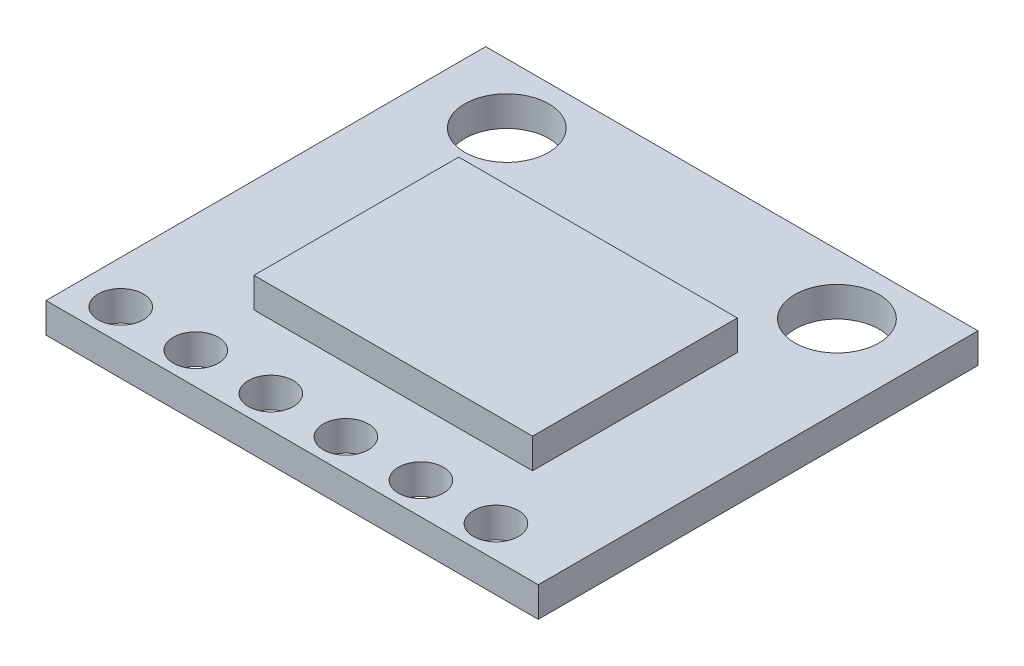
SolidWorks part; units mm, degrees
ref_plane "Front Plane" through (0, 0, 0) normal (0, 0, 1) x (1, 0, 0)
ref_plane "Top Plane" through (0, 0, 0) normal (0, 1, 0) x (1, 0, 0)
ref_plane "Right Plane" through (0, 0, 0) normal (1, 0, 0) x (0, 0, -1)
sketch "Sketch1" plane through (0, 0, 0) normal (0, 1, 0) x (1, 0, 0)
  line L1 (0, 0) -> (16.4, 0)
  line L2 (0, 0) -> (0, 14.65)
  line L3 (0, 14.65) -> (16.4, 14.65)
  line L4 (16.4, 0) -> (16.4, 14.65)
  dimension "D1" = 16.4
  dimension "D2" = 14.65
extrude "Boss-Extrude1" add sketch "Sketch1" along normal blind 1
sketch "Sketch2" plane through (0, 1, 0) normal (0, 1, 0) x (1, 0, 0)
  line L0 (2.7, 12.65) -> (13.7, 12.65) construction
  line L1 (8.2, 12.65) -> (8.2, 14.65) construction
  line L2 (16.4, 14.65) -> (0, 14.65) construction
  circle A0 centre (1.429, 1.0612) radius 0.75
  circle A1 centre (3.929, 1.0612) radius 0.75
  circle A2 centre (6.429, 1.0612) radius 0.75
  circle A3 centre (8.929, 1.0612) radius 0.75
  circle A4 centre (11.429, 1.0612) radius 0.75
  circle A5 centre (13.929, 1.0612) radius 0.75
  circle A6 centre (2.7, 12.65) radius 1.4
  circle A7 centre (13.7, 12.65) radius 1.4
  dimension "D1" = 1.5
  dimension "D3" = 2.8
  dimension "D4" = 11
  dimension "D5" = 2
  dimension "D2" = 6
extrude "Cut-Extrude1" cut sketch "Sketch2" against normal through all
sketch "Sketch3" plane through (0, 1, 0) normal (0, 1, 0) x (1, 0, 0)
  line L1 (3.7367, 10.0131) -> (13.0183, 10.0131)
  line L2 (3.7367, 10.0131) -> (3.7367, 3.1914)
  line L3 (3.7367, 3.1914) -> (13.0183, 3.1914)
  line L4 (13.0183, 10.0131) -> (13.0183, 3.1914)
extrude "Boss-Extrude2" add sketch "Sketch3" along normal blind 1
